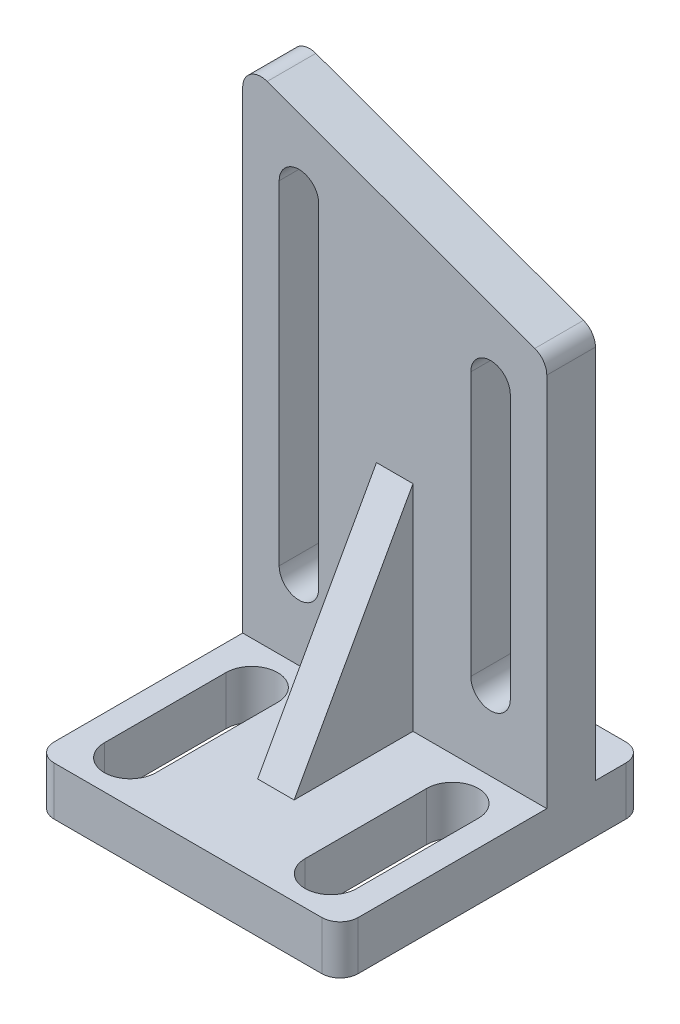
SolidWorks part; units mm, degrees
ref_plane "Front Plane" through (0, 0, 0) normal (0, 0, 1) x (1, 0, 0)
ref_plane "Top Plane" through (0, 0, 0) normal (0, 1, 0) x (1, 0, 0)
ref_plane "Right Plane" through (0, 0, 0) normal (1, 0, 0) x (0, 0, -1)
sketch "Sketch2" plane through (0, 0, 0) normal (0, 1, 0) x (1, 0, 0)
  line L1 (25, 25) -> (-25, 25)
  line L2 (25, 25) -> (25, -25)
  line L3 (25, -25) -> (-25, -25)
  line L4 (-25, 25) -> (-25, -25)
  line L5 (25, 25) -> (-25, -25) construction
  line L6 (25, -25) -> (-25, 25) construction
  point P0 (0, 0)
  dimension "D1" = 50
  dimension "D2" = 50
extrude "Boss-Extrude1" add sketch "Sketch2" along normal blind 8
sketch "Sketch5" plane through (0, 0, -25) normal (0, 0, -1) x (-1, 0, 0)
  line L0 (-25, 0) -> (-25, 71.8196)
  line L1 (-25, 71.8196) -> (25, 90.0181)
  line L2 (25, 90.0181) -> (25, 0)
  line L3 (25, 0) -> (-25, 0)
  dimension "D1" = 70
  dimension "D2" = 71.8196
extrude "Boss-Extrude2" add sketch "Sketch5" against normal blind 8 from offset 8 offset against normal yes
sketch "Sketch6" plane through (0, 8, 0) normal (0, 1, 0) x (1, 0, 0)
  line L0 (0, 0) -> (0, -10.2817) construction
  line L1 (-16.5, 2) -> (-16.5, -18) construction
  line L2 (-12.25, 2) -> (-12.25, -18)
  line L3 (-20.75, 2) -> (-20.75, -18)
  line L4 (-25, 9) -> (-25, -25) construction
  line L5 (25, -8) -> (12.5111, -8) construction
  line L6 (25, -25) -> (25, 9) construction
  line L7 (16.5, 2) -> (16.5, -18) construction
  line L8 (12.25, 2) -> (12.25, -18)
  line L9 (20.75, 2) -> (20.75, -18)
  arc A0 (-12.25, 2) -> (-20.75, 2) centre (-16.5, 2) ccw
  arc A1 (-20.75, -18) -> (-12.25, -18) centre (-16.5, -18) ccw
  arc A2 (12.25, 2) -> (20.75, 2) centre (16.5, 2) cw
  arc A3 (20.75, -18) -> (12.25, -18) centre (16.5, -18) cw
  point P5 (-16.5, -8)
  point P16 (0, 0)
  point P19 (16.5, -8)
  dimension "D1" = 8.5
  dimension "D2" = 20
  dimension "D3" = 8.5
extrude "Cut-Extrude2" cut sketch "Sketch6" against normal blind 8
sketch "Sketch7" plane through (25, 0, 0) normal (1, 0, 0) x (0, 0, -1)
  line L0 (9, 8) -> (-10.5434, 8)
  line L1 (-25, 8) -> (9, 8) construction
  line L2 (-10.5434, 8) -> (9, 43.2718)
  line L3 (9, 71.8196) -> (9, 8) construction
  line L4 (9, 43.2718) -> (9, 8)
extrude "Boss-Extrude3" add sketch "Sketch7" along normal blind 6 from offset 28 offset against normal yes
sketch "Sketch8" plane through (0, 0, -9) normal (0, 0, 1) x (1, 0, 0)
  line L0 (0, 0) -> (0, 67.9528) construction
  line L1 (-15.75, 75.4014) -> (-15.75, 20.5668) construction
  line L2 (-12.5, 75.4014) -> (-12.5, 20.5668)
  line L3 (-19, 75.4014) -> (-19, 20.5668)
  line L4 (15.75, 63.9363) -> (15.75, 20.5668) construction
  line L5 (19, 63.9363) -> (19, 20.5668)
  line L6 (12.5, 63.9363) -> (12.5, 20.5668)
  line L7 (-25, 8) -> (25, 8) construction
  line L8 (-25, 8) -> (-25, 90.0181) construction
  line L9 (15.75, 67.1863) -> (15.75, 75.1863) construction
  line L10 (-25, 90.0181) -> (25, 71.8196) construction
  line L11 (-15.75, 78.6514) -> (-15.75, 86.6514) construction
  arc A0 (-12.5, 75.4014) -> (-19, 75.4014) centre (-15.75, 75.4014) ccw
  arc A1 (-19, 20.5668) -> (-12.5, 20.5668) centre (-15.75, 20.5668) ccw
  arc A2 (19, 63.9363) -> (12.5, 63.9363) centre (15.75, 63.9363) ccw
  arc A3 (12.5, 20.5668) -> (19, 20.5668) centre (15.75, 20.5668) ccw
  point P5 (-15.75, 47.9841)
  point P12 (15.75, 42.2515)
  dimension "D1" = 6.5
  dimension "D2" = 8
  dimension "D5" = 12.5668
  dimension "D6" = 6
extrude "Cut-Extrude3" cut sketch "Sketch8" against normal through all
fillet "Fillet1" radius 3 6 edges at (25, 4, -25) (-25, 4, -25) (25, 4, 25) (-25, 4, 25) (25, 71.8196, -13) (-25, 90.0181, -13)
